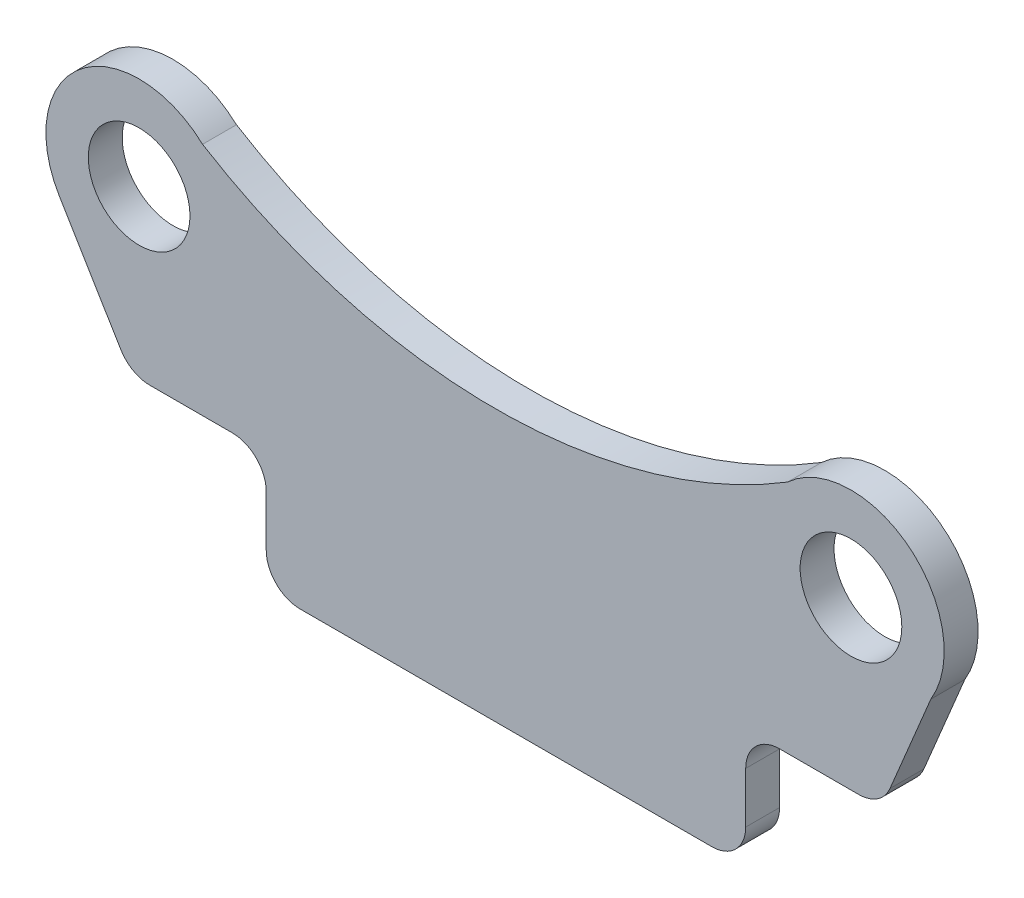
SolidWorks part; units mm, degrees
material "AISI 1020"
ref_plane "Ön Düzlem" through (0, 0, 0) normal (0, 0, 1) x (1, 0, 0)
ref_plane "Üst Düzlem" through (0, 0, 0) normal (0, 1, 0) x (1, 0, 0)
ref_plane "Sağ Düzlem" through (0, 0, 0) normal (1, 0, 0) x (0, 0, -1)
sketch "Çizim1" plane through (0, 0, 0) normal (0, 0, 1) x (1, 0, 0)
  line L0 (-47.125, -28.3591) -> (-10.8299, -88.6715)
  line L1 (6.3065, -98.3591) -> (55, -98.3591)
  line L2 (424.5623, -98.3591) -> (377.8823, -98.3591)
  line L3 (467.125, -28.3591) -> (443.0167, -86.0685)
  line L4 (75, -118.3591) -> (75, -148.3591)
  line L5 (95, -168.3591) -> (337.8823, -168.3591)
  line L6 (357.8823, -148.3591) -> (357.8823, -118.3591)
  arc A0 (37.4336, 40.2955) -> (-47.125, -28.3591) centre (0, 0) ccw
  arc A1 (467.125, -28.3591) -> (382.5664, 40.2955) centre (420, 0) ccw
  circle A2 centre (0, 0) radius 30
  circle A3 centre (420, 0) radius 30
  arc A4 (37.4336, 40.2955) -> (382.5664, 40.2955) centre (210, 321.4149) ccw
  arc A5 (337.8823, -168.3591) -> (357.8823, -148.3591) centre (337.8823, -148.3591) ccw
  arc A6 (75, -148.3591) -> (95, -168.3591) centre (95, -148.3591) ccw
  arc A7 (377.8823, -98.3591) -> (357.8823, -118.3591) centre (377.8823, -118.3591) ccw
  arc A8 (55, -98.3591) -> (75, -118.3591) centre (55, -118.3591) cw
  arc A9 (443.0167, -86.0685) -> (424.5623, -98.3591) centre (424.5623, -78.3591) cw
  arc A10 (-10.8299, -88.6715) -> (6.3065, -98.3591) centre (6.3065, -78.3591) ccw
  point P18 (75, -168.3591)
  point P21 (357.8823, -98.3591)
  point P24 (75, -98.3591)
  point P27 (437.8823, -98.3591)
  point P31 (-5, -98.3591)
  dimension "D1" = 110
  dimension "D2" = 110
  dimension "D3" = 60
  dimension "D4" = 60
  dimension "D10" = 70
  dimension "D11" = 20
  dimension "D5" = 420
  dimension "D6" = 70
  dimension "D7" = 70
  dimension "D8" = 80
  dimension "D9" = 80
extrude "Yükseklik-Ekstrüzyon1" add sketch "Çizim1" along normal blind 20
